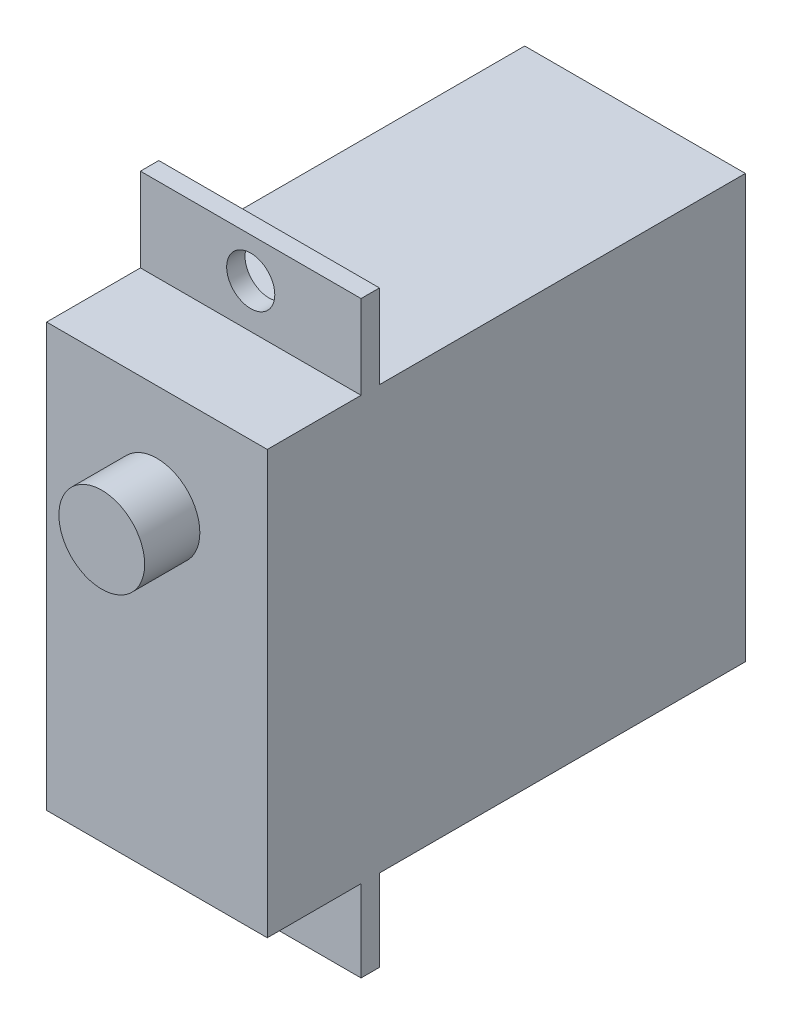
SolidWorks part; units mm, degrees
ref_plane "前视基准面" through (0, 0, 0) normal (0, 0, 1) x (1, 0, 0)
ref_plane "上视基准面" through (0, 0, 0) normal (0, 1, 0) x (1, 0, 0)
ref_plane "右视基准面" through (0, 0, 0) normal (1, 0, 0) x (0, 0, -1)
sketch "草图1" plane through (0, 0, 0) normal (0, 0, 1) x (1, 0, 0)
  line L1 (-1.4679, 13.3631) -> (10.5321, 13.3631)
  line L2 (-1.4679, 13.3631) -> (-1.4679, -9.6369)
  line L3 (-1.4679, -9.6369) -> (10.5321, -9.6369)
  line L4 (10.5321, 13.3631) -> (10.5321, -9.6369)
  dimension "D1" = 23
  dimension "D2" = 12
extrude "凸台-拉伸1" add sketch "草图1" along normal blind 26
sketch "草图2" plane through (0, 0, 26) normal (0, 0, 1) x (1, 0, 0)
  line L0 (4.5321, 12.5508) -> (4.5321, 9.3044) construction
  line L2 (10.5321, 13.3631) -> (-1.4679, 13.3631) construction
  circle A0 centre (4.5321, 7.6131) radius 2.3327
  dimension "D1" = 5.75
extrude "凸台-拉伸2" add sketch "草图2" along normal blind 3
sketch "草图3" plane through (10.5321, 0, 0) normal (1, 0, 0) x (0, 0, -1)
  line L0 (0, -9.6369) -> (0, 13.3631) construction
  line L1 (-20.9, 17.92) -> (-19.9, 17.92)
  line L2 (-20.9, 17.92) -> (-20.9, -14.08)
  line L3 (-20.9, -14.08) -> (-19.9, -14.08)
  line L4 (-19.9, 17.92) -> (-19.9, -14.08)
  line L5 (-20.9, 17.92) -> (-19.9, -14.08) construction
  line L6 (-20.9, -14.08) -> (-19.9, 17.92) construction
  point P0 (-20.4, 1.92)
  dimension "D1" = 19.9
  dimension "D2" = 32
  dimension "D3" = 1
extrude "凸台-拉伸3" add sketch "草图3" against normal up to surface (12 mm away) up to face at (-1.4679, 1.8631, 13)
sketch "草图4" plane through (0, 0, 20.9) normal (0, 0, 1) x (1, 0, 0)
  line L0 (4.5321, 17.92) -> (4.5321, 16.7182) construction
  circle A0 centre (4.5321, 15.753) radius 1.3083
  circle A1 centre (4.5321, -11.8279) radius 1.2297
extrude "切除-拉伸1" cut sketch "草图4" against normal blind 10
